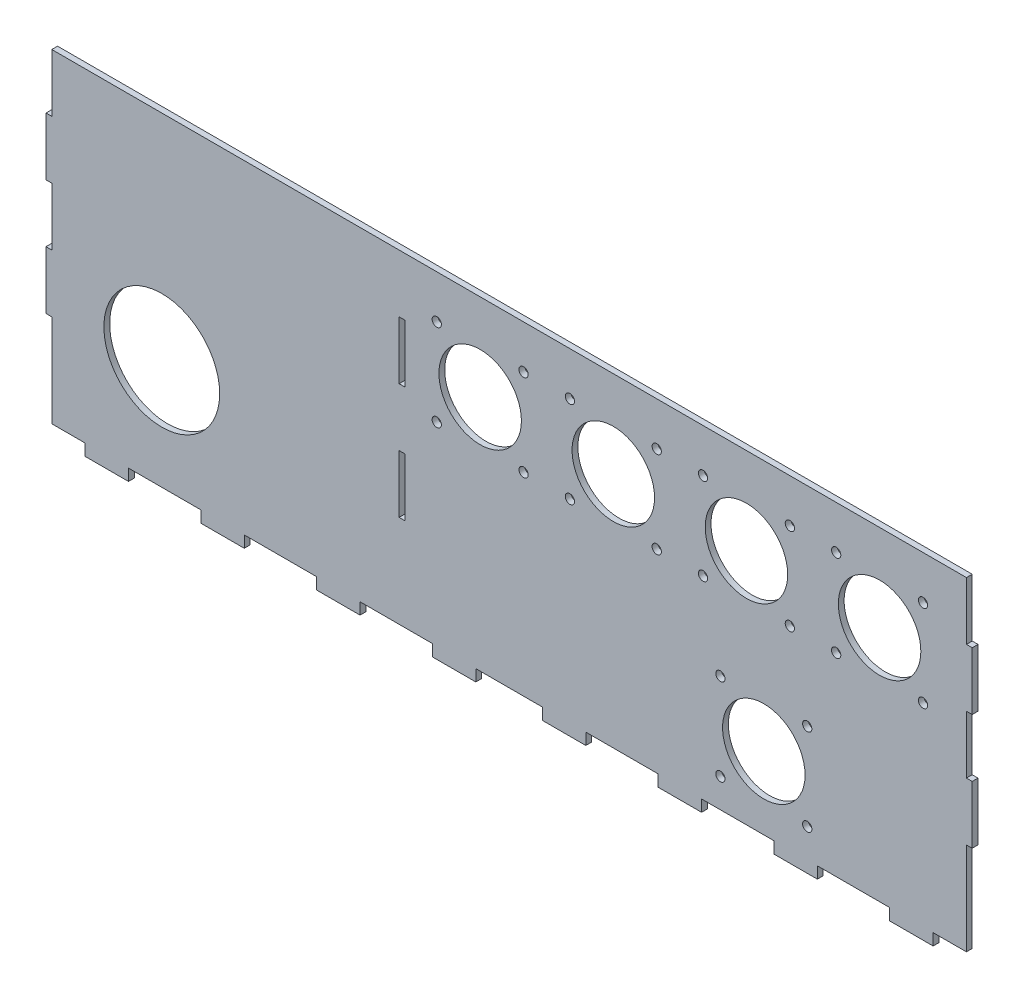
SolidWorks part; units mm, degrees
ref_plane "Front Plane" through (0, 0, 0) normal (0, 0, 1) x (1, 0, 0)
ref_plane "Top Plane" through (0, 0, 0) normal (0, 1, 0) x (1, 0, 0)
ref_plane "Right Plane" through (0, 0, 0) normal (1, 0, 0) x (0, 0, -1)
sketch "Sketch1" plane through (0, 0, 0) normal (0, 0, 1) x (1, 0, 0)
  line L1 (-158, -56) -> (-146.5, -56)
  line L2 (-158, -56) -> (-158, -24)
  line L3 (-158, 56) -> (-146.5, 56)
  line L4 (158, -56) -> (158, -24)
  line L5 (-158, -56) -> (158, 56) construction
  line L6 (-158, 56) -> (158, -56) construction
  line L15 (25, -49) -> (61, -13) construction
  line L18 (25, -13) -> (61, -49) construction
  line L20 (25, -49) -> (25, -13) construction
  line L21 (25, -49) -> (61, -49) construction
  line L22 (61, -49) -> (61, -13) construction
  line L23 (25, -13) -> (61, -13) construction
  line L28 (106, -49) -> (106, -13) construction
  line L29 (115, -49) -> (151, -49) construction
  line L30 (115, -49) -> (115, -13) construction
  line L31 (115, -13) -> (151, -13) construction
  line L32 (151, -49) -> (151, -13) construction
  line L33 (115, -49) -> (151, -13) construction
  line L34 (115, -13) -> (151, -49) construction
  line L35 (70, -49) -> (106, -13) construction
  line L36 (70, -13) -> (106, -13) construction
  line L37 (70, -13) -> (106, -49) construction
  line L38 (70, -49) -> (70, -13) construction
  line L39 (70, -49) -> (106, -49) construction
  line L40 (-106.5, -56) -> (-106.5, -60)
  line L42 (-146.5, -56) -> (-146.5, -60)
  line L43 (-146.5, -60) -> (-131.5, -60)
  line L44 (-131.5, -56) -> (-131.5, -60)
  line L46 (-91.5, -56) -> (-91.5, -60)
  line L47 (-106.5, -60) -> (-91.5, -60)
  line L48 (-66.5, -56) -> (-66.5, -60)
  line L50 (-51.5, -56) -> (-51.5, -60)
  line L51 (-66.5, -60) -> (-51.5, -60)
  line L52 (-26.5, -56) -> (-26.5, -60)
  line L54 (-11.5, -56) -> (-11.5, -60)
  line L55 (-26.5, -60) -> (-11.5, -60)
  line L56 (0, -64.9) -> (0, 64.9) construction
  line L58 (11.5, -56) -> (11.5, -60)
  line L59 (26.5, -60) -> (11.5, -60)
  line L60 (26.5, -56) -> (26.5, -60)
  line L62 (51.5, -56) -> (51.5, -60)
  line L63 (66.5, -60) -> (51.5, -60)
  line L64 (66.5, -56) -> (66.5, -60)
  line L66 (91.5, -56) -> (91.5, -60)
  line L67 (106.5, -60) -> (91.5, -60)
  line L68 (106.5, -56) -> (106.5, -60)
  line L69 (146.5, -60) -> (131.5, -60)
  line L70 (131.5, -56) -> (131.5, -60)
  line L72 (146.5, -56) -> (146.5, -60)
  line L73 (146.5, -56) -> (158, -56)
  line L74 (106.5, -56) -> (131.5, -56)
  line L75 (66.5, -56) -> (91.5, -56)
  line L76 (26.5, -56) -> (51.5, -56)
  line L77 (-11.5, -56) -> (11.5, -56)
  line L79 (-51.5, -56) -> (-26.5, -56)
  line L80 (-158, 36) -> (-160, 36)
  line L81 (-131.5, -56) -> (-106.5, -56)
  line L82 (-91.5, -56) -> (-66.5, -56)
  line L84 (-158, 16) -> (-160, 16)
  line L85 (-160, 36) -> (-160, 16)
  line L86 (-158, -4) -> (-160, -4)
  line L87 (-160, -4) -> (-160, -24)
  line L88 (-158, -24) -> (-160, -24)
  line L89 (158, -4) -> (160, -4)
  line L90 (160, -4) -> (160, -24)
  line L91 (158, -24) -> (160, -24)
  line L93 (158, 16) -> (160, 16)
  line L94 (160, 36) -> (160, 16)
  line L95 (158, 36) -> (160, 36)
  line L97 (-158, 36) -> (-158, 56)
  line L98 (-158, -4) -> (-158, 16)
  line L99 (158, 36) -> (158, 56)
  line L100 (158, -4) -> (158, 16)
  line L101 (-38, -24) -> (-38, -4)
  line L102 (-38, 16) -> (-36, 16)
  line L103 (-38, 16) -> (-38, 36)
  line L104 (-38, 36) -> (-36, 36)
  line L105 (-36, 16) -> (-36, 36)
  line L106 (-38, -24) -> (-36, -24)
  line L107 (-36, -24) -> (-36, -4)
  line L108 (-38, -4) -> (-36, -4)
  line L125 (176, 0) -> (-176, 0) construction
  line L150 (-131.5, 56) -> (-106.5, 56)
  line L151 (-91.5, 56) -> (-66.5, 56)
  line L152 (-51.5, 56) -> (-26.5, 56)
  line L153 (-11.5, 56) -> (11.5, 56)
  line L154 (26.5, 56) -> (51.5, 56)
  line L155 (146.5, 56) -> (158, 56)
  line L156 (106.5, 56) -> (131.5, 56)
  line L157 (66.5, 56) -> (91.5, 56)
  line L175 (11.5, 56) -> (11.5, 58)
  line L176 (26.5, 56) -> (26.5, 58)
  line L177 (11.5, 58) -> (26.5, 58)
  line L179 (51.5, 56) -> (51.5, 58)
  line L180 (66.5, 56) -> (66.5, 58)
  line L181 (51.5, 58) -> (66.5, 58)
  line L183 (91.5, 56) -> (91.5, 58)
  line L184 (106.5, 56) -> (106.5, 58)
  line L185 (91.5, 58) -> (106.5, 58)
  line L187 (131.5, 56) -> (131.5, 58)
  line L188 (146.5, 56) -> (146.5, 58)
  line L189 (131.5, 58) -> (146.5, 58)
  line L192 (-66.5, 56) -> (-66.5, 58)
  line L193 (-66.5, 58) -> (-51.5, 58)
  line L194 (-51.5, 56) -> (-51.5, 58)
  line L196 (-106.5, 56) -> (-106.5, 58)
  line L197 (-106.5, 58) -> (-91.5, 58)
  line L198 (-91.5, 56) -> (-91.5, 58)
  line L200 (-146.5, 56) -> (-146.5, 58)
  line L201 (-146.5, 58) -> (-131.5, 58)
  line L202 (-131.5, 56) -> (-131.5, 58)
  line L204 (-26.5, 56) -> (-26.5, 58)
  line L205 (-26.5, 58) -> (-11.5, 58)
  line L206 (-11.5, 56) -> (-11.5, 58)
  circle A0 centre (-120, -18) radius 20
  circle A16 centre (133, -31) radius 14.25 construction
  circle A17 centre (118, -16) radius 1.6 construction
  circle A18 centre (148, -16) radius 1.6 construction
  circle A19 centre (118, -46) radius 1.6 construction
  circle A20 centre (148, -46) radius 1.6 construction
  circle A21 centre (88, -31) radius 14.25
  circle A22 centre (73, -16) radius 1.6
  circle A23 centre (103, -16) radius 1.6
  circle A24 centre (73, -46) radius 1.6
  circle A25 centre (103, -46) radius 1.6
  circle A26 centre (8, -29) radius 6 construction
  circle A27 centre (8, -49) radius 6 construction
  circle A30 centre (-24, -29) radius 6 construction
  circle A31 centre (-24, -49) radius 6 construction
  circle A32 centre (43, -31) radius 14.25 construction
  circle A33 centre (28, -16) radius 1.6 construction
  circle A34 centre (58, -16) radius 1.6 construction
  circle A35 centre (28, -46) radius 1.6 construction
  circle A36 centre (58, -46) radius 1.6 construction
  point P0 (0, 0)
  point P19 (133, -31)
  dimension "D3" = 40
  dimension "D8" = 2
  dimension "D9" = 12
  dimension "D10" = 20
  dimension "D21" = 28.5
  dimension "D22" = 3.2
  dimension "D23" = 3.2
  dimension "D11" = 12
  dimension "D12" = 2
  dimension "D13" = 32
  dimension "D1" = 316
  dimension "D2" = 112
  dimension "D4" = 38
  dimension "D5" = 38
  dimension "D14" = 85
  dimension "D15" = 150
  dimension "D18" = 45
  dimension "D19" = 36
  dimension "D20" = 36
  dimension "D24" = 30
  dimension "D25" = 15
  dimension "D26" = 15
  dimension "D27" = 15
  dimension "D28" = 25
  dimension "D29" = 25
  dimension "D30" = 30
  dimension "D32" = 45
  dimension "D33" = 11.5
  dimension "D34" = 15
  dimension "D36" = 4
  dimension "D37" = 25
  dimension "D38" = 20
  dimension "D39" = 20
  dimension "D40" = 2
  dimension "D42" = 20
  dimension "D43" = 120
  dimension "D44" = 2
  dimension "D45" = 20
  dimension "D46" = 20
  dimension "D48" = 20
  dimension "D61" = 2
  dimension "D63" = 2
  dimension "D65" = 15
  dimension "D66" = 2
  dimension "D67" = 90
  dimension "D68" = 15
  dimension "D69" = 2
  dimension "D70" = 15
  dimension "D71" = 2
  dimension "D72" = 90
  dimension "D73" = 15
  dimension "D74" = 2
  dimension "D62" = 2
  dimension "D76" = 2
  dimension "D17" = 2
  dimension "D31" = 2
  dimension "D35" = 4
  dimension "D41" = 2
  dimension "D47" = 2
extrude "Boss-Extrude1" add sketch "Sketch1" along normal blind 2
sketch "Sketch2" plane through (0, 0, 2) normal (0, 0, 1) x (1, 0, 0)
  line L0 (73, -12.9) -> (73, 44.9) construction
  line L1 (83.5, -9.5218) -> (83.5, 10.1905)
  line L2 (55.5, 16) -> (90.5, 16) construction
  line L3 (55.5, 5.5) -> (55.5, 26.5) construction
  line L4 (90.5, 5.5) -> (90.5, 26.5) construction
  line L5 (62.5, -9.5218) -> (62.5, 10.1905)
  line L6 (62.5, -12.9) -> (62.5, 44.9) construction
  line L7 (83.5, -12.9) -> (83.5, 44.9) construction
  line L8 (62.5, 21.8095) -> (62.5, 41.5218)
  line L9 (83.5, 21.8095) -> (83.5, 41.5218)
  line L10 (91.5, 56) -> (66.5, 56) construction
  line L11 (158, -4) -> (158, 16) construction
  line L12 (-7.5, -9.5218) -> (-7.5, 10.1905)
  line L13 (-7.5, 21.8095) -> (-7.5, 41.5218)
  line L14 (13.5, 21.8095) -> (13.5, 41.5218)
  line L15 (13.5, -9.5218) -> (13.5, 10.1905)
  line L16 (3, -12.9) -> (3, 44.9) construction
  line L17 (-14.5, 16) -> (20.5, 16) construction
  line L18 (-14.5, 5.5) -> (-14.5, 26.5) construction
  line L19 (20.5, 5.5) -> (20.5, 26.5) construction
  circle A0 centre (73, 16) radius 32.5 construction
  arc A2 (62.5, 21.8095) -> (62.5, 10.1905) centre (73, 16) ccw
  circle A3 centre (55.5, 5.5) radius 2.6
  circle A4 centre (55.5, 26.5) radius 2.6
  circle A5 centre (90.5, 26.5) radius 2.6
  circle A6 centre (90.5, 5.5) radius 2.6
  arc A7 (63.868, -11.4193) -> (82.132, -11.4193) centre (73, 16) ccw
  arc A8 (83.5, 10.1905) -> (83.5, 21.8095) centre (73, 16) ccw
  arc A9 (82.132, 43.4193) -> (63.868, 43.4193) centre (73, 16) ccw
  arc A10 (63.868, 43.4193) -> (62.5, 41.5218) centre (64.5, 41.5218) ccw
  arc A11 (82.132, 43.4193) -> (83.5, 41.5218) centre (81.5, 41.5218) cw
  arc A12 (83.5, -9.5218) -> (82.132, -11.4193) centre (81.5, -9.5218) cw
  arc A13 (63.868, -11.4193) -> (62.5, -9.5218) centre (64.5, -9.5218) cw
  arc A14 (-6.132, -11.4193) -> (-7.5, -9.5218) centre (-5.5, -9.5218) cw
  arc A15 (-7.5, 21.8095) -> (-7.5, 10.1905) centre (3, 16) ccw
  arc A16 (-6.132, 43.4193) -> (-7.5, 41.5218) centre (-5.5, 41.5218) ccw
  arc A17 (12.132, 43.4193) -> (-6.132, 43.4193) centre (3, 16) ccw
  arc A18 (12.132, 43.4193) -> (13.5, 41.5218) centre (11.5, 41.5218) cw
  arc A19 (13.5, 10.1905) -> (13.5, 21.8095) centre (3, 16) ccw
  arc A20 (13.5, -9.5218) -> (12.132, -11.4193) centre (11.5, -9.5218) cw
  arc A21 (-6.132, -11.4193) -> (12.132, -11.4193) centre (3, 16) ccw
  circle A22 centre (-14.5, 26.5) radius 2.6
  circle A23 centre (-14.5, 5.5) radius 2.6
  circle A24 centre (3, 16) radius 32.5 construction
  circle A25 centre (20.5, 26.5) radius 2.6
  circle A26 centre (20.5, 5.5) radius 2.6
  point P6 (73, 16)
  point P9 (55.5, 16)
  point P12 (90.5, 16)
  point P19 (73, 16)
  point P20 (73, 16)
  point P35 (83.5, 42.9251)
  dimension "D1" = 65
  dimension "D2" = 24
  dimension "D4" = 5.2
  dimension "D7" = 5.2
  dimension "D8" = 5.2
  dimension "D9" = 5.2
  dimension "D13" = 57.8
  dimension "D14" = 40
  dimension "D12" = 2
  dimension "D3" = 35
  dimension "D5" = 21
  dimension "D6" = 21
  dimension "D10" = 10.5
  dimension "D15" = 85
  dimension "D17" = 70
  dimension "D11" = 10.5
  dimension "D16" = 2
extrude "Cut-Extrude1" [suppressed] cut sketch "Sketch2" against normal blind 10
sketch "Sketch3" plane through (0, 0, 2) normal (0, 0, 1) x (1, 0, 0)
  line L0 (158, -4) -> (158, 16) construction
  line L1 (131.5, 56) -> (106.5, 56) construction
  circle A0 centre (116, -4) radius 6
  circle A1 centre (148, -4) radius 6
  dimension "D1" = 12
  dimension "D2" = 12
  dimension "D3" = 32
  dimension "D5" = 60
  dimension "D4" = 10
extrude "Cut-Extrude2" [suppressed] cut sketch "Sketch3" against normal blind 10
sketch "Sketch4" plane through (0, 0, 2) normal (0, 0, 1) x (1, 0, 0)
  line L0 (66.5, 56) -> (66.5, 58) construction
  line L1 (-146.5, 58) -> (-131.5, 58)
  line L2 (-146.5, 58) -> (-146.5, 56)
  line L3 (-146.5, 56) -> (-131.5, 56)
  line L4 (-131.5, 58) -> (-131.5, 56)
  line L5 (-106.5, 58) -> (-91.5, 58)
  line L6 (-106.5, 58) -> (-106.5, 56)
  line L7 (-106.5, 56) -> (-91.5, 56)
  line L8 (-91.5, 58) -> (-91.5, 56)
  line L9 (-66.5, 58) -> (-51.5, 58)
  line L10 (-66.5, 58) -> (-66.5, 56)
  line L11 (-66.5, 56) -> (-51.5, 56)
  line L12 (-51.5, 58) -> (-51.5, 56)
  line L13 (-26.5, 58) -> (-11.5, 58)
  line L14 (-26.5, 58) -> (-26.5, 56)
  line L15 (-26.5, 56) -> (-11.5, 56)
  line L16 (-11.5, 58) -> (-11.5, 56)
  line L17 (11.5, 58) -> (26.5, 58)
  line L18 (11.5, 58) -> (11.5, 56)
  line L19 (11.5, 56) -> (26.5, 56)
  line L20 (26.5, 58) -> (26.5, 56)
  line L21 (51.5, 58) -> (66.5, 58)
  line L22 (51.5, 58) -> (51.5, 56)
  line L23 (51.5, 56) -> (66.5, 56)
  line L24 (66.5, 58) -> (66.5, 56)
  line L25 (91.5, 56) -> (66.5, 56) construction
  line L26 (158, 56) -> (146.5, 56) construction
  line L27 (91.5, 58) -> (106.5, 58)
  line L28 (91.5, 58) -> (91.5, 56)
  line L29 (91.5, 56) -> (106.5, 56)
  line L30 (106.5, 58) -> (106.5, 56)
  line L31 (131.5, 58) -> (146.5, 58)
  line L32 (131.5, 58) -> (131.5, 56)
  line L33 (131.5, 56) -> (146.5, 56)
  line L34 (146.5, 58) -> (146.5, 56)
  line L35 (146.5, 56) -> (146.5, 58) construction
extrude "Cut-Extrude3" cut sketch "Sketch4" against normal through all both and the other way through all
sketch "Sketch5" plane through (0, 0, 2) normal (0, 0, 1) x (1, 0, 0)
  line L1 (110, 8) -> (146, 8) construction
  line L2 (110, 8) -> (110, 44) construction
  line L3 (110, 44) -> (146, 44) construction
  line L4 (146, 8) -> (146, 44) construction
  line L5 (110, 8) -> (146, 44) construction
  line L6 (110, 44) -> (146, 8) construction
  line L7 (146.5, 56) -> (158, 56) construction
  line L8 (158, 36) -> (158, 56) construction
  line L9 (64, 44) -> (100, 8) construction
  line L10 (64, 8) -> (100, 44) construction
  line L11 (64, 44) -> (100, 44) construction
  line L12 (100, 8) -> (100, 44) construction
  line L13 (64, 8) -> (100, 8) construction
  line L14 (64, 8) -> (64, 44) construction
  line L15 (18, 44) -> (54, 8) construction
  line L16 (18, 8) -> (54, 44) construction
  line L17 (18, 44) -> (54, 44) construction
  line L18 (54, 8) -> (54, 44) construction
  line L19 (18, 8) -> (54, 8) construction
  line L20 (18, 8) -> (18, 44) construction
  line L21 (-28, 44) -> (8, 8) construction
  line L22 (-28, 8) -> (8, 44) construction
  line L23 (-28, 44) -> (8, 44) construction
  line L24 (8, 8) -> (8, 44) construction
  line L25 (-28, 8) -> (8, 8) construction
  line L26 (-28, 8) -> (-28, 44) construction
  circle A0 centre (128, 26) radius 14.25
  circle A1 centre (113, 41) radius 1.6
  circle A2 centre (143, 41) radius 1.6
  circle A3 centre (143, 11) radius 1.6
  circle A4 centre (113, 11) radius 1.6
  circle A5 centre (82, 26) radius 14.25
  circle A6 centre (97, 11) radius 1.6
  circle A7 centre (67, 11) radius 1.6
  circle A8 centre (67, 41) radius 1.6
  circle A9 centre (97, 41) radius 1.6
  circle A10 centre (36, 26) radius 14.25
  circle A11 centre (51, 11) radius 1.6
  circle A12 centre (21, 11) radius 1.6
  circle A13 centre (21, 41) radius 1.6
  circle A14 centre (51, 41) radius 1.6
  circle A15 centre (-10, 26) radius 14.25
  circle A16 centre (5, 11) radius 1.6
  circle A17 centre (-25, 11) radius 1.6
  circle A18 centre (-25, 41) radius 1.6
  circle A19 centre (5, 41) radius 1.6
  point P0 (128, 26)
  point P17 (82, 26)
  point P35 (36, 26)
  point P50 (-10, 26)
  dimension "D3" = 28.5
  dimension "D4" = 3.2
  dimension "D5" = 3.2
  dimension "D6" = 3.2
  dimension "D7" = 3.2
  dimension "D1" = 36
  dimension "D2" = 36
  dimension "D8" = 15
  dimension "D9" = 30
  dimension "D10" = 15
  dimension "D11" = 30
  dimension "D12" = 30
  dimension "D13" = 30
  dimension "D15" = 46
  dimension "D14" = 4
extrude "Cut-Extrude4" cut sketch "Sketch5" against normal through all both and the other way through all
